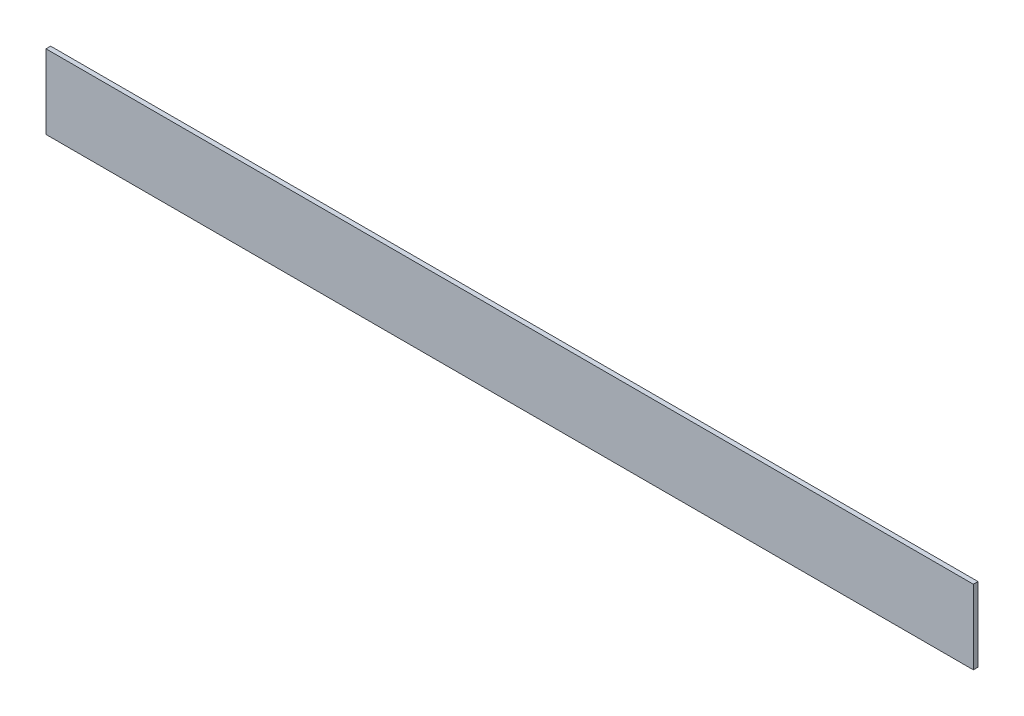
SolidWorks part; units mm, degrees
material "Nylon 101"
ref_plane "Front Plane" through (0, 0, 0) normal (0, 0, 1) x (1, 0, 0)
ref_plane "Top Plane" through (0, 0, 0) normal (0, 1, 0) x (1, 0, 0)
ref_plane "Right Plane" through (0, 0, 0) normal (1, 0, 0) x (0, 0, -1)
sketch "Sketch1" plane through (0, 0, 0) normal (0, 0, 1) x (1, 0, 0)
  line L6 (0, 0) -> (-317.5, 0)
  line L7 (0, 0) -> (0, -25.4)
  line L8 (0, -25.4) -> (-317.5, -25.4)
  line L9 (-317.5, 0) -> (-317.5, -25.4)
  dimension "D1" = 25.4
  dimension "D2" = 317.5
extrude "Boss-Extrude1" add sketch "Sketch1" along normal blind 1.5875
ref_plane "Plane1" through (0, -12.7, 0) normal (0, 1, 0) x (1, 0, 0)
